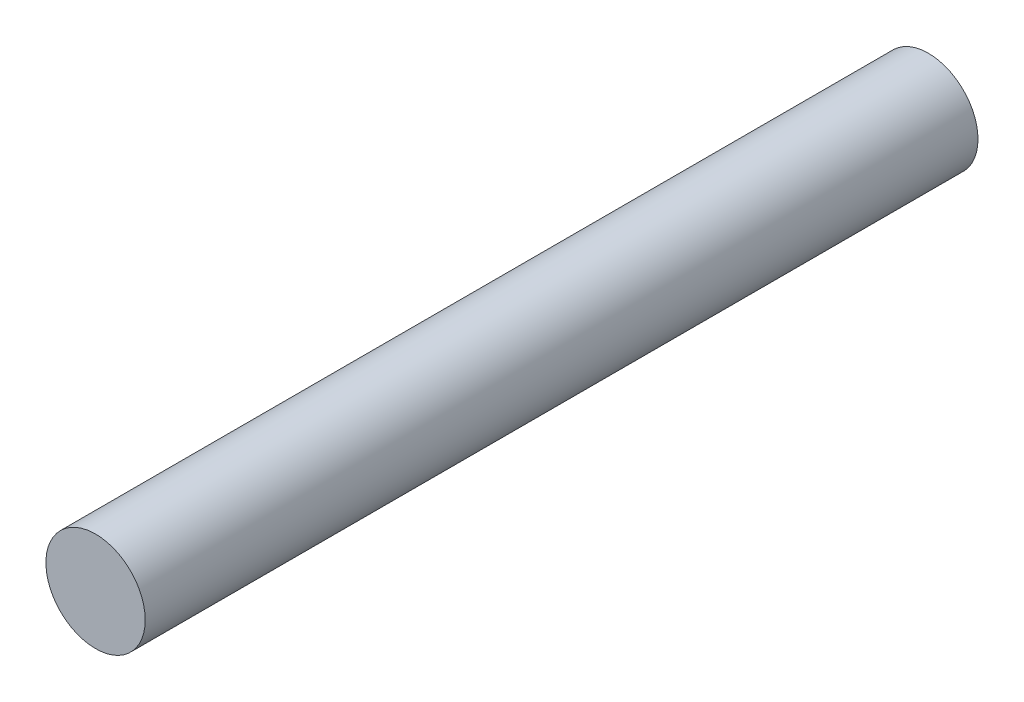
SolidWorks part; units mm, degrees
ref_plane "Front Plane" through (0, 0, 0) normal (0, 0, 1) x (1, 0, 0)
ref_plane "Top Plane" through (0, 0, 0) normal (0, 1, 0) x (1, 0, 0)
ref_plane "Right Plane" through (0, 0, 0) normal (1, 0, 0) x (0, 0, -1)
sketch "Sketch1" plane through (0, 0, 0) normal (0, 0, 1) x (1, 0, 0)
  circle A0 centre (0, 0) radius 1.58
  dimension "D1" = 3.16
extrude "Boss-Extrude1" add sketch "Sketch1" along normal blind 26.5 contours A0
